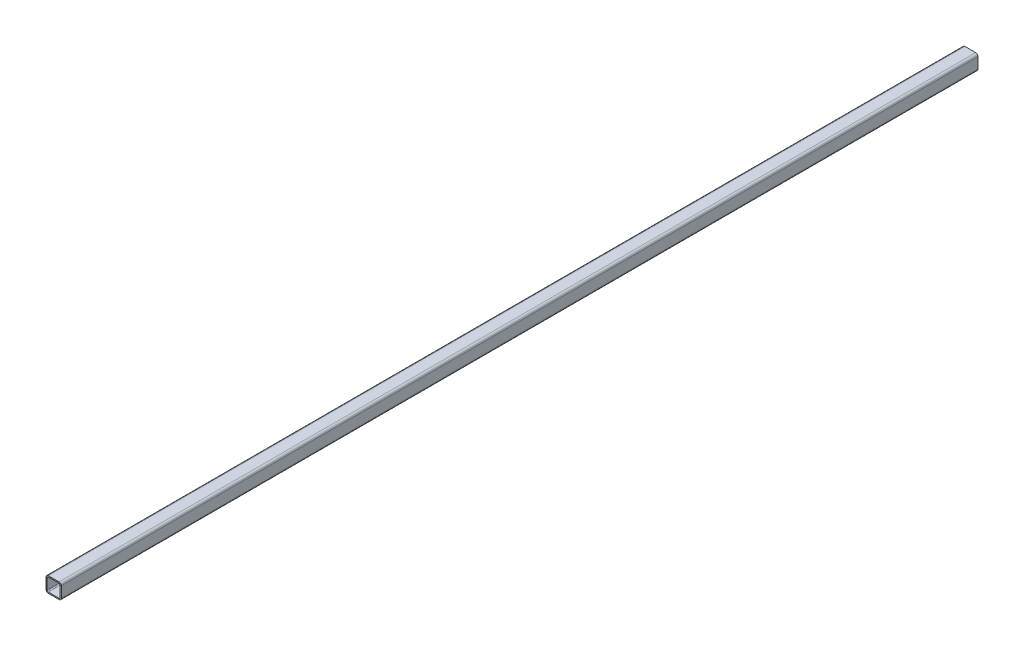
SolidWorks part; units mm, degrees
material "AISI 304"
ref_plane "Front Plane" through (0, 0, 0) normal (0, 0, 1) x (1, 0, 0)
ref_plane "Top Plane" through (0, 0, 0) normal (0, 1, 0) x (1, 0, 0)
ref_plane "Right Plane" through (0, 0, 0) normal (1, 0, 0) x (0, 0, -1)
sketch "Эскиз1" plane through (0, 0, 0) normal (0, 0, 1) x (1, 0, 0)
  line L0 (-14, 17) -> (14, 17)
  line L1 (-14, 20) -> (14, 20)
  line L2 (-20, 14) -> (-20, -14)
  line L3 (-14, -20) -> (14, -20)
  line L4 (20, 14) -> (20, -14)
  line L5 (-20, 20) -> (20, -20) construction
  line L6 (-20, -20) -> (20, 20) construction
  line L7 (17, 14) -> (17, -14)
  line L8 (-14, -17) -> (14, -17)
  line L9 (-17, 14) -> (-17, -14)
  arc A0 (14, 20) -> (20, 14) centre (14, 14) cw
  arc A1 (14, -20) -> (20, -14) centre (14, -14) ccw
  arc A2 (-20, -14) -> (-14, -20) centre (-14, -14) ccw
  arc A3 (-14, 20) -> (-20, 14) centre (-14, 14) ccw
  arc A4 (14, 17) -> (17, 14) centre (14, 14) cw
  arc A5 (14, -17) -> (17, -14) centre (14, -14) ccw
  arc A6 (-17, -14) -> (-14, -17) centre (-14, -14) ccw
  arc A7 (-14, 17) -> (-17, 14) centre (-14, 14) ccw
  point P0 (0, 0)
  dimension "D1" = 6
  dimension "D2" = 40
  dimension "D3" = 40
  dimension "D4" = 3
extrude "Бобышка-Вытянуть1" add sketch "Эскиз1" along normal mid plane 2393
